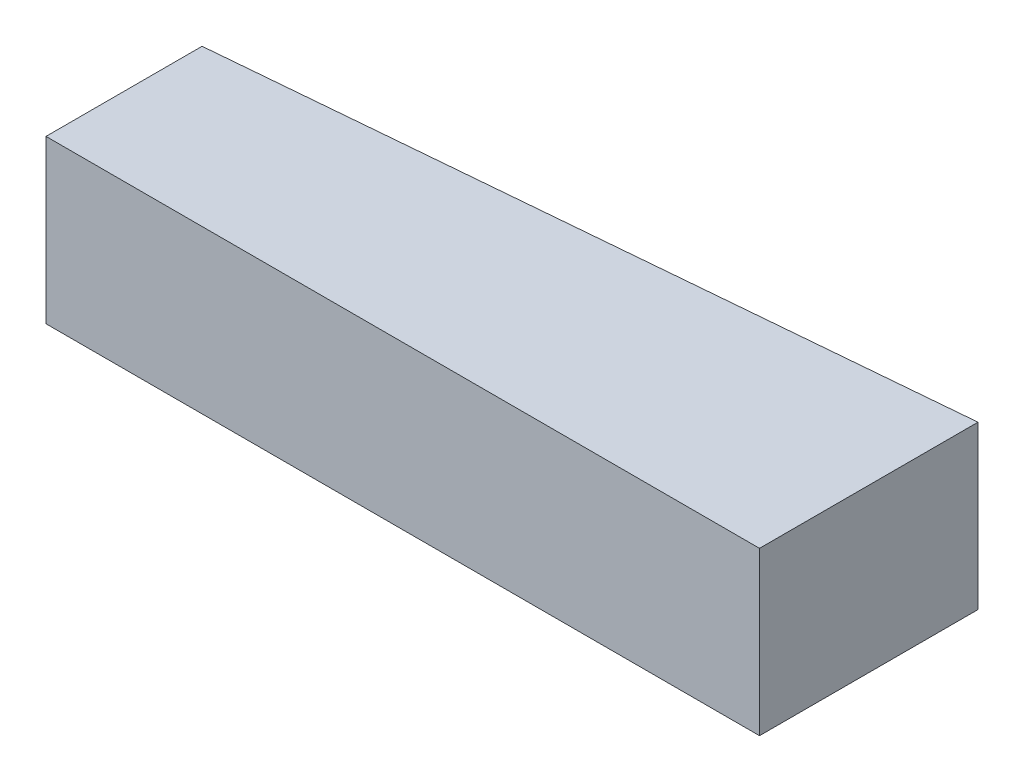
SolidWorks part; units mm, degrees
material "White Acrylic"
ref_plane "Front" through (0, 0, 0) normal (0, 0, 1) x (1, 0, 0)
ref_plane "Top" through (0, 0, 0) normal (0, 1, 0) x (1, 0, 0)
ref_plane "Right" through (0, 0, 0) normal (1, 0, 0) x (0, 0, -1)
sketch "Sketch2" plane through (0, 0, 0) normal (0, 1, 0) x (1, 0, 0)
  line L0 (0, 0) -> (0, 2.5)
  line L1 (0, 2.5) -> (11.4301, 3.5)
  line L2 (11.4301, 3.5) -> (11.4301, 0)
  line L3 (11.4301, 0) -> (0, 0)
  dimension "D1" = 2.5
  dimension "D2" = 3.5
  dimension "D3" = 5
  dimension "D4" = 11.4301
extrude "Boss-Extrude1" add sketch "Sketch2" along normal blind 2.6
